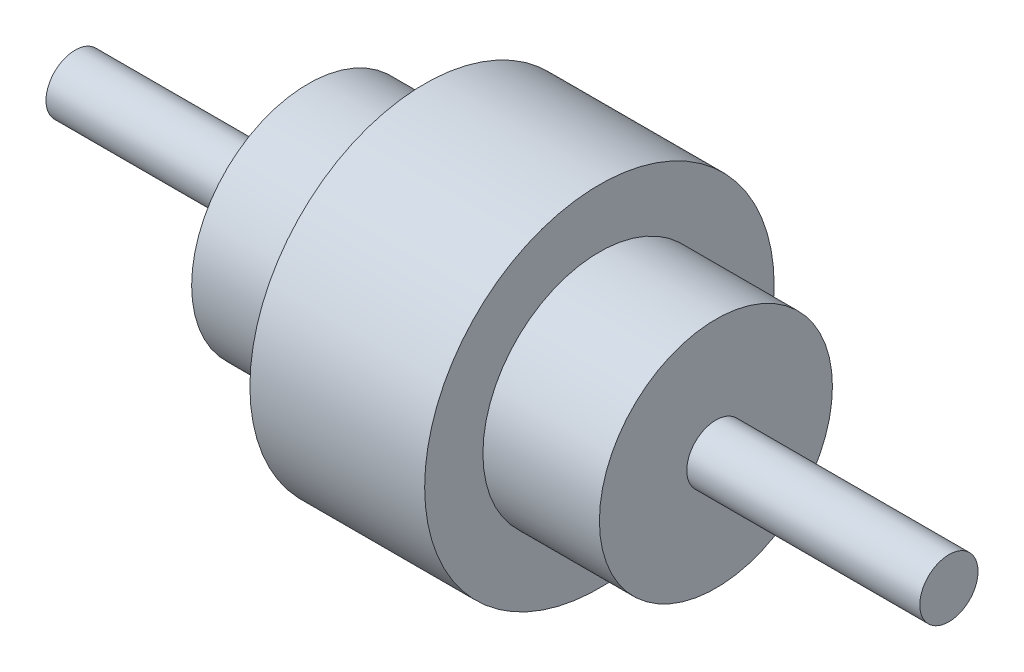
SolidWorks part; units mm, degrees
ref_plane "Front Plane" through (0, 0, 0) normal (0, 0, 1) x (1, 0, 0)
ref_plane "Top Plane" through (0, 0, 0) normal (0, 1, 0) x (1, 0, 0)
ref_plane "Right Plane" through (0, 0, 0) normal (1, 0, 0) x (0, 0, -1)
sketch "Sketch1" plane through (0, 0, 0) normal (0, 1, 0) x (1, 0, 0)
  line L0 (0, 0) -> (300, 0)
  line L1 (300, 0) -> (300, -10)
  line L2 (300, -10) -> (220, -10)
  line L3 (220, -10) -> (220, -40)
  line L4 (120, -40) -> (120, -60)
  line L5 (220, -40) -> (180, -40)
  line L6 (180, -40) -> (180, -60)
  line L7 (180, -60) -> (120, -60)
  line L8 (80, -40) -> (120, -40)
  line L9 (80, -10) -> (80, -40)
  line L10 (0, -10) -> (80, -10)
  line L11 (0, 0) -> (0, -10)
  point P3 (0, 0)
  point P7 (260, -10)
  point P12 (0, 0)
  point P16 (0, 0)
  point P17 (0, 0)
  point P18 (0, -5)
  dimension "D1" = 300
  dimension "D2" = 10
  dimension "D3" = 30
  dimension "D4" = 40
  dimension "D5" = 40
  dimension "D6" = 60
  dimension "D7" = 50
revolve "Revolve1" add sketch "Sketch1" angle 360 about L0
